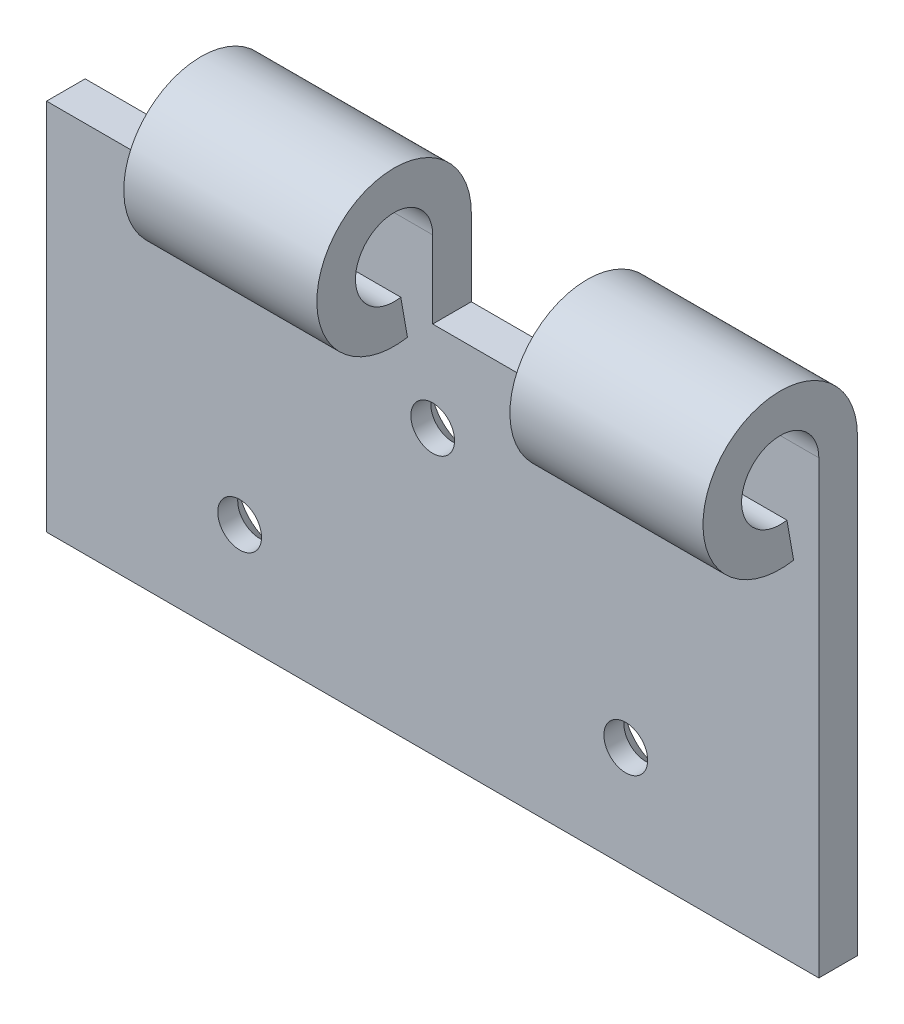
SolidWorks part; units mm, degrees
material "PET"
ref_plane "Front Plane" through (0, 0, 0) normal (0, 0, 1) x (1, 0, 0)
ref_plane "Top Plane" through (0, 0, 0) normal (0, 1, 0) x (1, 0, 0)
ref_plane "Right Plane" through (0, 0, 0) normal (1, 0, 0) x (0, 0, -1)
sketch "Sketch1" plane through (0, 0, 0) normal (0, 0, 1) x (1, 0, 0)
  line L1 (-30, -17.5) -> (30, -17.5)
  line L2 (-30, -17.5) -> (-30, 17.5)
  line L3 (-30, 17.5) -> (30, 17.5)
  line L4 (30, -17.5) -> (30, 17.5)
  line L5 (-30, -17.5) -> (30, 17.5) construction
  line L6 (-30, 17.5) -> (30, -17.5) construction
  point P0 (0, 0)
  dimension "D2" = 35
  dimension "D3" = 60
extrude "Boss-Extrude1" add sketch "Sketch1" along normal blind 3
sketch "Sketch5" plane through (30, 0, 0) normal (1, 0, 0) x (0, 0, -1)
  line L0 (0, 17.5) -> (-6, 17.5) construction
  line L1 (0, -17.5) -> (0, 17.5) construction
  line L2 (-6, 17.5) -> (-5.4791, 14.5456) construction
  line L5 (-3, -17.5) -> (-3, 17.5) construction
  line L6 (-5.4791, 14.5456) -> (-4.9581, 11.5912)
  line L7 (-3, 17.5) -> (-3, 12.3038)
  arc A0 (-3, 12.3038) -> (-4.9581, 11.5912) centre (-6, 17.5) ccw
  arc A1 (-3, 17.5) -> (-5.4791, 14.5456) centre (-6, 17.5) ccw
  circle A2 centre (-6, 17.5) radius 3 construction
  circle A3 centre (-6, 17.5) radius 6 construction
  dimension "D1" = 6
  dimension "D3" = 80
  dimension "D2" = 3
extrude "Boss-Extrude2" add sketch "Sketch5" against normal up to surface (60 mm away) up to face at (-30, 0, 1.5)
sketch "Sketch9" plane through (-12, 0, 3) normal (0, 0, -1) x (-1, 0, 0)
  line L6 (18, 23.5) -> (-42, 23.5) construction
  line L9 (-27, 23.5) -> (-12, 23.5)
  line L11 (-27, 23.5) -> (-27, 11.5)
  line L13 (-27, 11.5) -> (-12, 11.5)
  line L19 (-12, 23.5) -> (-12, 11.5)
  line L20 (18, -17.5) -> (18, 17.5) construction
  line L21 (3, 23.5) -> (18, 23.5)
  line L22 (3, 23.5) -> (3, 11.5)
  line L23 (3, 11.5) -> (18, 11.5)
  line L24 (18, 23.5) -> (18, 11.5)
  dimension "D1" = 15
  dimension "D2" = 15
  dimension "D3" = 12
extrude "Cut-Extrude4" cut sketch "Sketch9" along normal through all both and the other way through all
sketch "Sketch2" plane through (0, 0, 0) normal (0, 0, 1) x (1, 0, 0)
  line L0 (-15, 17.5) -> (0, 17.5) construction
  line L1 (0, -6.6) -> (0, 6.6) construction
  point P0 (0, 4.5)
  point P2 (-15, -9.5)
  point P10 (0, 0)
  point P11 (0, 0)
  point P12 (0, 0)
  point P15 (0, 0)
  point P16 (15, -9.5)
  dimension "D1" = 14
  dimension "D2" = 30
  dimension "D6" = 13
hole_wizard "CSK for M3 Countersunk Flat Head Screw1" positions "Sketch2" profile "Sketch3" countersink size "M3" standard "ISO"
sketch "Sketch3" plane through (0, 4.5, 0) normal (1, 0, 0) x (0, 1, 0)
  line L0 (0, 0) -> (0, 4.0215)
  line L1 (0, 4.0215) -> (1.7, 3)
  line L2 (1.7, 3) -> (1.7, 1.45)
  line L3 (1.7, 1.45) -> (3.15, 0)
  line L5 (3.15, 0) -> (0, 0)
  line L6 (-1.7, 1.45) -> (-3.15, 0) construction
  line L10 (0, 4.0215) -> (-1.7, 3) construction
  line L11 (0, -6.35) -> (0, 107.95) construction
  dimension "Hole Dia." = 3.4
  dimension "Hole Depth" = 3
  dimension "Near C'Sink Dia." = 6.3
  dimension "Near C'Sink Angle" = 90
  dimension "Drill Angle" = 118
